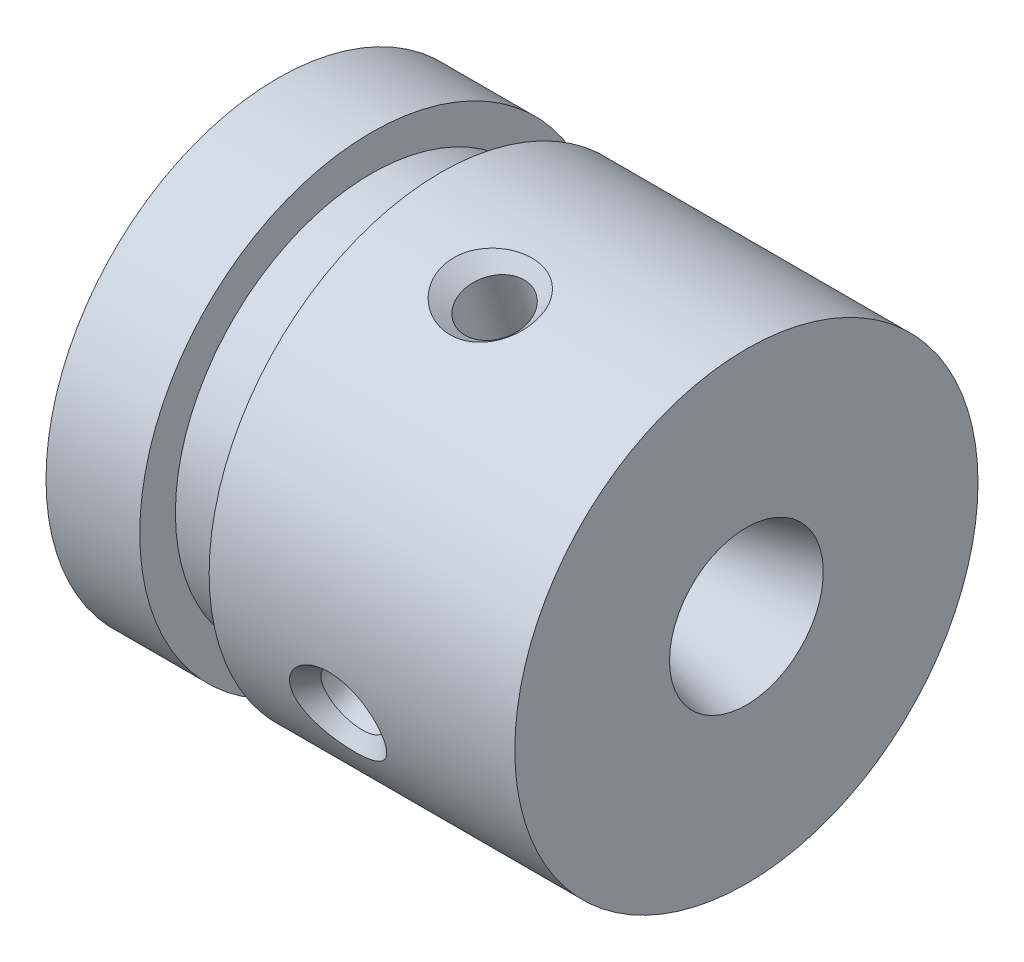
SolidWorks part; units mm, degrees
material "AISI 304"
ref_plane "Front Plane" through (0, 0, 0) normal (0, 0, 1) x (1, 0, 0)
ref_plane "Top Plane" through (0, 0, 0) normal (0, 1, 0) x (1, 0, 0)
ref_plane "Right Plane" through (0, 0, 0) normal (1, 0, 0) x (0, 0, -1)
sketch "Sketch2" plane through (0, 0, 0) normal (0, 1, 0) x (1, 0, 0)
  line L0 (-6.7935, 0) -> (10.7145, 0) construction
  line L1 (-15.3406, 4) -> (-4.7608, 4)
  line L2 (-4.7608, 4) -> (-0.3645, 1.95)
  line L3 (-0.3645, 1.95) -> (1.6355, 1.95)
  line L4 (1.6355, 1.95) -> (9.6594, 4.1)
  line L5 (-15.3406, 4) -> (-15.3406, 12.35)
  line L6 (-15.3406, 12.35) -> (9.6594, 12.35)
  line L7 (9.6594, 12.35) -> (9.6594, 4.1)
  dimension "D1" = 1.95
  dimension "D2" = 4.1
  dimension "D3" = 15
  dimension "D4" = 25
  dimension "D5" = 12.35
  dimension "D6" = 4
  dimension "D7" = 2
  dimension "D8" = 25
revolve "Revolve2" add sketch "Sketch2" angle 360 about L0
hole_wizard "M4x0.7 Tapped Hole1" positions "3DSketch1" profile "Sketch3" tap size "M4x0.7" standard "ANSI Metric"
sketch3d "3DSketch1"
  line L0 (-15.3406, 11.7877, 3.684) -> (9.6594, 11.7877, 3.684)
  circle A0 centre (-15.3406, 0, 0) radius 12.35 construction
  circle A1 centre (9.6594, 0, 0) radius 12.35 construction
  point P0 (-2.4533, 12.0795, 2.5706)
  point P1 (-0.3406, 11.7877, 3.684)
  point P8 (-27.6906, 0, 0)
  point P11 (-2.6906, 0, 0)
  dimension "D1" = 10
sketch "Sketch3" plane through (-0.3406, 11.7877, 3.684) normal (1, 0, 0) x (0, -0.2983, 0.9545)
  line L0 (0, 0) -> (0, 7.9914)
  line L1 (0, 7.9914) -> (1.65, 7)
  line L2 (1.65, 7) -> (1.65, 0.85)
  line L3 (1.65, 0.85) -> (2.5, 0)
  line L5 (2.5, 0) -> (0, 0)
  line L6 (-1.65, 0.85) -> (-2.5, 0) construction
  line L10 (0, 7.9914) -> (-1.65, 7) construction
  line L11 (0, -6.35) -> (0, 107.95) construction
  dimension "Tap Drill Dia." = 3.3
  dimension "Tap Drill Depth" = 7
  dimension "Near C'Sink Dia." = 5
  dimension "Near C'Sink Angle" = 90
  dimension "Drill Angle" = 118
cosmetic thread "Hole Thread6" parameters "D1"=6, "D2"=4
cosmetic thread "Hole Thread7" parameters "D1"=6, "D2"=4
pattern_circular "CirPattern1" count 4 over 360 about axis through (-6.7935, 0, 0) along (-1, 0, 0) of "M4x0.7 Tapped Hole1"
cosmetic thread "Hole Thread8" parameters "D1"=6, "D2"=4
cosmetic thread "Hole Thread9" parameters "D1"=6, "D2"=4
cosmetic thread "Hole Thread10" parameters "D1"=6, "D2"=4
cosmetic thread "Hole Thread11" parameters "D1"=6, "D2"=4
cosmetic thread "Hole Thread12" parameters "D1"=6, "D2"=4
cosmetic thread "Hole Thread13" parameters "D1"=6, "D2"=4
sketch "Sketch4" plane through (0, 0, 0) normal (0, 1, 0) x (1, 0, 0)
  line L0 (-10.3406, 12.35) -> (-10.3406, 10.45)
  line L1 (9.6594, 12.35) -> (-15.3406, 12.35) construction
  line L2 (-10.3406, 10.45) -> (-6.6406, 10.45)
  line L3 (-6.6406, 10.45) -> (-6.6406, 12.35)
  line L4 (-15.3406, 12.35) -> (-15.3406, -12.35) construction
  line L5 (-10.3406, 12.35) -> (-6.6406, 12.35)
  line L7 (-15.3406, 0) -> (9.6594, 0) construction
  line L8 (9.6594, -12.35) -> (9.6594, 12.35) construction
  dimension "D1" = 5
  dimension "D2" = 3.7
  dimension "D3" = 1.9
revolve "Cut-Revolve1" cut sketch "Sketch4" angle 360 about L7
